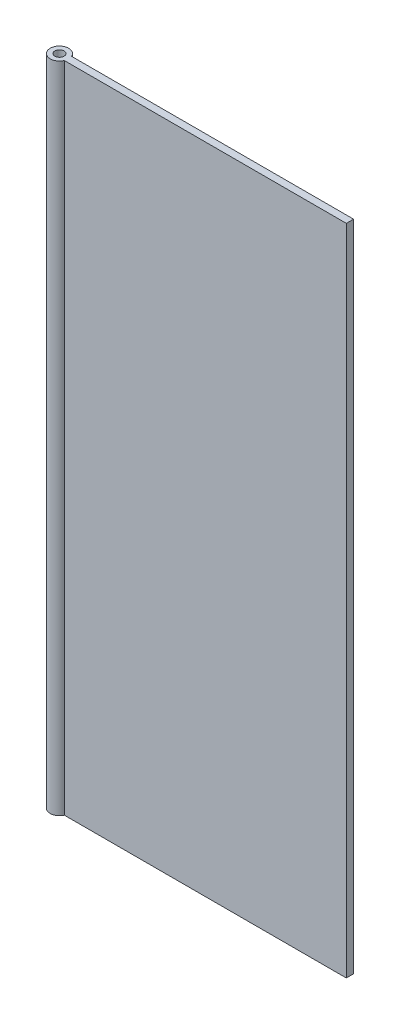
SolidWorks part; units mm, degrees
ref_plane "Front Plane" through (0, 0, 0) normal (0, 0, 1) x (1, 0, 0)
ref_plane "Top Plane" through (0, 0, 0) normal (0, 1, 0) x (1, 0, 0)
ref_plane "Right Plane" through (0, 0, 0) normal (1, 0, 0) x (0, 0, -1)
curve "Curve1"
  spline degree 3 poles (0.9998, 0, 0) (1.0001, 0, 0) (0.9998, 0, 0) (0.9995, 0.0001, 0) (0.9989, 0.0002, 0) (0.9982, 0.0004, 0) (0.9972, 0.0006, 0) (0.996, 0.0009, 0) (0.9946, 0.0012, 0) (0.9929, 0.0015, 0) (0.9911, 0.0019, 0) (0.989, 0.0023, 0) (0.9867, 0.0028, 0) (0.9842, 0.0033, 0) (0.9815, 0.0039, 0) (0.9786, 0.0045, 0) (0.9755, 0.0051, 0) (0.9721, 0.0058, 0) (0.9686, 0.0065, 0) (0.9648, 0.0073, 0) (0.9609, 0.0081, 0) (0.9567, 0.009, 0) (0.9523, 0.0098, 0) (0.9478, 0.0107, 0) (0.943, 0.0117, 0) (0.9381, 0.0127, 0) (0.9329, 0.0137, 0) (0.9276, 0.0147, 0) (0.9221, 0.0158, 0) (0.9164, 0.0169, 0) (0.9105, 0.018, 0) (0.9045, 0.0192, 0) (0.8982, 0.0204, 0) (0.8918, 0.0216, 0) (0.8852, 0.0228, 0) (0.8784, 0.024, 0) (0.8715, 0.0253, 0) (0.8644, 0.0266, 0) (0.8572, 0.0279, 0) (0.8498, 0.0292, 0) (0.8422, 0.0306, 0) (0.8345, 0.0319, 0) (0.8267, 0.0333, 0) (0.8187, 0.0347, 0) (0.8105, 0.0361, 0) (0.8023, 0.0375, 0) (0.7939, 0.0389, 0) (0.7853, 0.0403, 0) (0.7767, 0.0417, 0) (0.7679, 0.0431, 0) (0.759, 0.0446, 0) (0.75, 0.046, 0) (0.7408, 0.0474, 0) (0.7316, 0.0489, 0) (0.7223, 0.0503, 0) (0.7129, 0.0517, 0) (0.7033, 0.0531, 0) (0.6937, 0.0546, 0) (0.684, 0.056, 0) (0.6743, 0.0574, 0) (0.6644, 0.0588, 0) (0.6545, 0.0601, 0) (0.6445, 0.0615, 0) (0.6344, 0.0629, 0) (0.6243, 0.0642, 0) (0.6142, 0.0655, 0) (0.6039, 0.0668, 0) (0.5937, 0.0681, 0) (0.5834, 0.0694, 0) (0.573, 0.0706, 0) (0.5627, 0.0718, 0) (0.5523, 0.073, 0) (0.5418, 0.0742, 0) (0.5314, 0.0753, 0) (0.5209, 0.0764, 0) (0.5105, 0.0774, 0) (0.5, 0.0785, 0) (0.4895, 0.0795, 0) (0.4791, 0.0804, 0) (0.4686, 0.0813, 0) (0.4582, 0.0822, 0) (0.4477, 0.083, 0) (0.4373, 0.0838, 0) (0.427, 0.0846, 0) (0.4166, 0.0853, 0) (0.4063, 0.0859, 0) (0.3961, 0.0865, 0) (0.3858, 0.0871, 0) (0.3757, 0.0876, 0) (0.3656, 0.088, 0) (0.3555, 0.0884, 0) (0.3455, 0.0887, 0) (0.3356, 0.089, 0) (0.3257, 0.0892, 0) (0.316, 0.0894, 0) (0.3063, 0.0894, 0) (0.2967, 0.0895, 0) (0.2871, 0.0894, 0) (0.2777, 0.0893, 0) (0.2684, 0.0892, 0) (0.2592, 0.089, 0) (0.25, 0.0887, 0) (0.241, 0.0883, 0) (0.2321, 0.0879, 0) (0.2233, 0.0874, 0) (0.2147, 0.0868, 0) (0.2061, 0.0862, 0) (0.1977, 0.0855, 0) (0.1895, 0.0847, 0) (0.1813, 0.0839, 0) (0.1733, 0.083, 0) (0.1655, 0.0821, 0) (0.1578, 0.081, 0) (0.1502, 0.0799, 0) (0.1428, 0.0788, 0) (0.1356, 0.0776, 0) (0.1285, 0.0763, 0) (0.1215, 0.0749, 0) (0.1148, 0.0735, 0) (0.1082, 0.072, 0) (0.1018, 0.0705, 0) (0.0955, 0.0689, 0) (0.0895, 0.0673, 0) (0.0836, 0.0656, 0) (0.0779, 0.0638, 0) (0.0724, 0.062, 0) (0.067, 0.0601, 0) (0.0619, 0.0582, 0) (0.0569, 0.0562, 0) (0.0522, 0.0542, 0) (0.0476, 0.0522, 0) (0.0433, 0.05, 0) (0.0391, 0.0479, 0) (0.0351, 0.0457, 0) (0.0314, 0.0434, 0) (0.0278, 0.0412, 0) (0.0245, 0.0388, 0) (0.0214, 0.0365, 0) (0.0184, 0.0341, 0) (0.0157, 0.0317, 0) (0.0132, 0.0292, 0) (0.0109, 0.0267, 0) (0.0089, 0.0241, 0) (0.007, 0.0216, 0) (0.0053, 0.019, 0) (0.0039, 0.0164, 0) (0.0027, 0.0137, 0) (0.0017, 0.011, 0) (0.001, 0.0083, 0) (0.0004, 0.0056, 0) (0.0001, 0.0028, 0) (0, 0, 0) (0.0001, -0.0028, 0) (0.0004, -0.0056, 0) (0.001, -0.0083, 0) (0.0017, -0.011, 0) (0.0027, -0.0137, 0) (0.0039, -0.0164, 0) (0.0053, -0.019, 0) (0.007, -0.0216, 0) (0.0089, -0.0241, 0) (0.0109, -0.0267, 0) (0.0132, -0.0292, 0) (0.0157, -0.0317, 0) (0.0184, -0.0341, 0) (0.0214, -0.0365, 0) (0.0245, -0.0388, 0) (0.0278, -0.0412, 0) (0.0314, -0.0434, 0) (0.0351, -0.0457, 0) (0.0391, -0.0479, 0) (0.0433, -0.05, 0) (0.0476, -0.0522, 0) (0.0522, -0.0542, 0) (0.0569, -0.0562, 0) (0.0619, -0.0582, 0) (0.067, -0.0601, 0) (0.0724, -0.062, 0) (0.0779, -0.0638, 0) (0.0836, -0.0656, 0) (0.0895, -0.0673, 0) (0.0955, -0.0689, 0) (0.1018, -0.0705, 0) (0.1082, -0.072, 0) (0.1148, -0.0735, 0) (0.1215, -0.0749, 0) (0.1285, -0.0763, 0) (0.1356, -0.0776, 0) (0.1428, -0.0788, 0) (0.1502, -0.0799, 0) (0.1578, -0.081, 0) (0.1655, -0.0821, 0) (0.1733, -0.083, 0) (0.1813, -0.0839, 0) (0.1895, -0.0847, 0) (0.1977, -0.0855, 0) (0.2061, -0.0862, 0) (0.2147, -0.0868, 0) (0.2233, -0.0874, 0) (0.2321, -0.0879, 0) (0.241, -0.0883, 0) (0.25, -0.0887, 0) (0.2592, -0.089, 0) (0.2684, -0.0892, 0) (0.2777, -0.0893, 0) (0.2871, -0.0894, 0) (0.2967, -0.0895, 0) (0.3063, -0.0894, 0) (0.316, -0.0894, 0) (0.3257, -0.0892, 0) (0.3356, -0.089, 0) (0.3455, -0.0887, 0) (0.3555, -0.0884, 0) (0.3656, -0.088, 0) (0.3757, -0.0876, 0) (0.3858, -0.0871, 0) (0.3961, -0.0865, 0) (0.4063, -0.0859, 0) (0.4166, -0.0853, 0) (0.427, -0.0846, 0) (0.4373, -0.0838, 0) (0.4477, -0.083, 0) (0.4582, -0.0822, 0) (0.4686, -0.0813, 0) (0.4791, -0.0804, 0) (0.4895, -0.0795, 0) (0.5, -0.0785, 0) (0.5105, -0.0774, 0) (0.5209, -0.0764, 0) (0.5314, -0.0753, 0) (0.5418, -0.0742, 0) (0.5523, -0.073, 0) (0.5627, -0.0718, 0) (0.573, -0.0706, 0) (0.5834, -0.0694, 0) (0.5937, -0.0681, 0) (0.6039, -0.0668, 0) (0.6142, -0.0655, 0) (0.6243, -0.0642, 0) (0.6344, -0.0629, 0) (0.6445, -0.0615, 0) (0.6545, -0.0601, 0) (0.6644, -0.0588, 0) (0.6743, -0.0574, 0) (0.684, -0.056, 0) (0.6937, -0.0546, 0) (0.7033, -0.0531, 0) (0.7129, -0.0517, 0) (0.7223, -0.0503, 0) (0.7316, -0.0489, 0) (0.7408, -0.0474, 0) (0.75, -0.046, 0) (0.759, -0.0446, 0) (0.7679, -0.0431, 0) (0.7767, -0.0417, 0) (0.7853, -0.0403, 0) (0.7939, -0.0389, 0) (0.8023, -0.0375, 0) (0.8105, -0.0361, 0) (0.8187, -0.0347, 0) (0.8267, -0.0333, 0) (0.8345, -0.0319, 0) (0.8422, -0.0306, 0) (0.8498, -0.0292, 0) (0.8572, -0.0279, 0) (0.8644, -0.0266, 0) (0.8715, -0.0253, 0) (0.8784, -0.024, 0) (0.8852, -0.0228, 0) (0.8918, -0.0216, 0) (0.8982, -0.0204, 0) (0.9045, -0.0192, 0) (0.9105, -0.018, 0) (0.9164, -0.0169, 0) (0.9221, -0.0158, 0) (0.9276, -0.0147, 0) (0.9329, -0.0137, 0) (0.9381, -0.0127, 0) (0.943, -0.0117, 0) (0.9478, -0.0107, 0) (0.9523, -0.0098, 0) (0.9567, -0.009, 0) (0.9609, -0.0081, 0) (0.9648, -0.0073, 0) (0.9686, -0.0065, 0) (0.9721, -0.0058, 0) (0.9755, -0.0051, 0) (0.9786, -0.0045, 0) (0.9815, -0.0039, 0) (0.9842, -0.0033, 0) (0.9867, -0.0028, 0) (0.989, -0.0023, 0) (0.9911, -0.0019, 0) (0.9929, -0.0015, 0) (0.9946, -0.0012, 0) (0.996, -0.0009, 0) (0.9972, -0.0006, 0) (0.9982, -0.0004, 0) (0.9989, -0.0002, 0) (0.9995, -0.0001, 0) (0.9998, 0, 0) (1.0001, 0, 0) (0.9998, 0, 0) knots -0.000486 -0.000216 -0.000054 0 0.000054 0.000216 0.000486 0.000863 0.001349 0.001941 0.002641 0.003447 0.00436 0.005379 0.006503 0.007732 0.009066 0.010503 0.012043 0.013685 0.01543 0.017274 0.019219 0.021263 0.023405 0.025644 0.027978 0.030408 0.032932 0.035548 0.038256 0.041054 0.04394 0.046915 0.049975 0.053121 0.05635 0.059661 0.063052 0.066522 0.07007 0.073693 0.077391 0.08116 0.085001 0.088911 0.092888 0.09693 0.101036 0.105204 0.109431 0.113717 0.118059 0.122455 0.126904 0.131403 0.135949 0.140543 0.14518 0.149859 0.154579 0.159336 0.164129 0.168955 0.173814 0.178701 0.183616 0.188555 0.193518 0.198501 0.203502 0.20852 0.213551 0.218594 0.223647 0.228706 0.233771 0.238839 0.243907 0.248973 0.254036 0.259092 0.26414 0.269178 0.274203 0.279214 0.284207 0.289181 0.294134 0.299064 0.303968 0.308845 0.313692 0.318508 0.323291 0.328038 0.332747 0.337418 0.342047 0.346633 0.351175 0.35567 0.360116 0.364513 0.368858 0.37315 0.377387 0.381568 0.38569 0.389754 0.393756 0.397696 0.401573 0.405385 0.409131 0.412809 0.41642 0.41996 0.42343 0.426829 0.430155 0.433407 0.436586 0.439689 0.442717 0.445669 0.448545 0.451343 0.454064 0.456707 0.459273 0.461761 0.464171 0.466505 0.468761 0.470942 0.473048 0.47508 0.47704 0.478929 0.480749 0.482504 0.484195 0.485826 0.487402 0.488926 0.490404 0.491842 0.493245 0.49462 0.495975 0.497318 0.498657 0.5 0.501343 0.502682 0.504025 0.50538 0.506755 0.508158 0.509596 0.511074 0.512598 0.514174 0.515805 0.517496 0.519251 0.521071 0.52296 0.52492 0.526952 0.529058 0.531239 0.533495 0.535829 0.538239 0.540727 0.543293 0.545936 0.548657 0.551455 0.554331 0.557283 0.560311 0.563414 0.566593 0.569845 0.573171 0.57657 0.58004 0.58358 0.587191 0.590869 0.594615 0.598427 0.602304 0.606244 0.610246 0.61431 0.618432 0.622613 0.62685 0.631142 0.635487 0.639884 0.64433 0.648825 0.653367 0.657953 0.662582 0.667253 0.671962 0.676709 0.681492 0.686308 0.691155 0.696032 0.700936 0.705866 0.710819 0.715793 0.720786 0.725797 0.730822 0.73586 0.740908 0.745964 0.751027 0.756093 0.761161 0.766229 0.771294 0.776353 0.781406 0.786449 0.79148 0.796498 0.801499 0.806482 0.811445 0.816384 0.821299 0.826186 0.831045 0.835871 0.840664 0.845421 0.850141 0.85482 0.859457 0.864051 0.868597 0.873096 0.877545 0.881941 0.886283 0.890569 0.894796 0.898964 0.90307 0.907112 0.911089 0.914999 0.91884 0.922609 0.926307 0.92993 0.933478 0.936948 0.940339 0.94365 0.946879 0.950025 0.953085 0.95606 0.958946 0.961744 0.964452 0.967068 0.969592 0.972022 0.974356 0.976595 0.978737 0.980781 0.982726 0.98457 0.986315 0.987957 0.989497 0.990934 0.992268 0.993497 0.994621 0.99564 0.996553 0.997359 0.998059 0.998651 0.999137 0.999514 0.999784 0.999946 1 1.000054 1.000216 1.000486 periodic
sketch "Sketch1" plane through (0, 0, 0) normal (0, 0, 1) x (1, 0, 0)
  line L1 (0, 341.9254) -> (200, 341.9254)
  line L2 (0, 341.9254) -> (0, -108.0746)
  line L3 (0, -108.0746) -> (200, -108.0746)
  line L4 (200, 341.9254) -> (200, -108.0746)
  dimension "D1" = 450
  dimension "D2" = 200
extrude "Boss-Extrude1" add sketch "Sketch1" along normal mid plane 5
sketch "Sketch2" plane through (0, 0, 0) normal (0, 1, 0) x (1, 0, 0)
  circle A0 centre (0, 0) radius 6.35
  dimension "D1" = 12.7
extrude "Boss-Extrude2" add sketch "Sketch2" along normal up to surface and the other way up to surface up to face at (100, 341.9254, 0) other way up to face at (100, -108.0746, 0)
sketch "Sketch3" plane through (0, 341.9254, 0) normal (0, 1, 0) x (1, 0, 0)
  circle A0 centre (0, 0) radius 3.175
extrude "Cut-Extrude1" cut sketch "Sketch3" against normal through all
equation "\"theta1\"= 20deg"
equation "\"theta2\"= 10deg"
equation "\"theta3\"= 10deg"
equation "\"h\"= 2m"
equation "\"l\"= 0.5m"
equation "\"mast\"= 2in"
